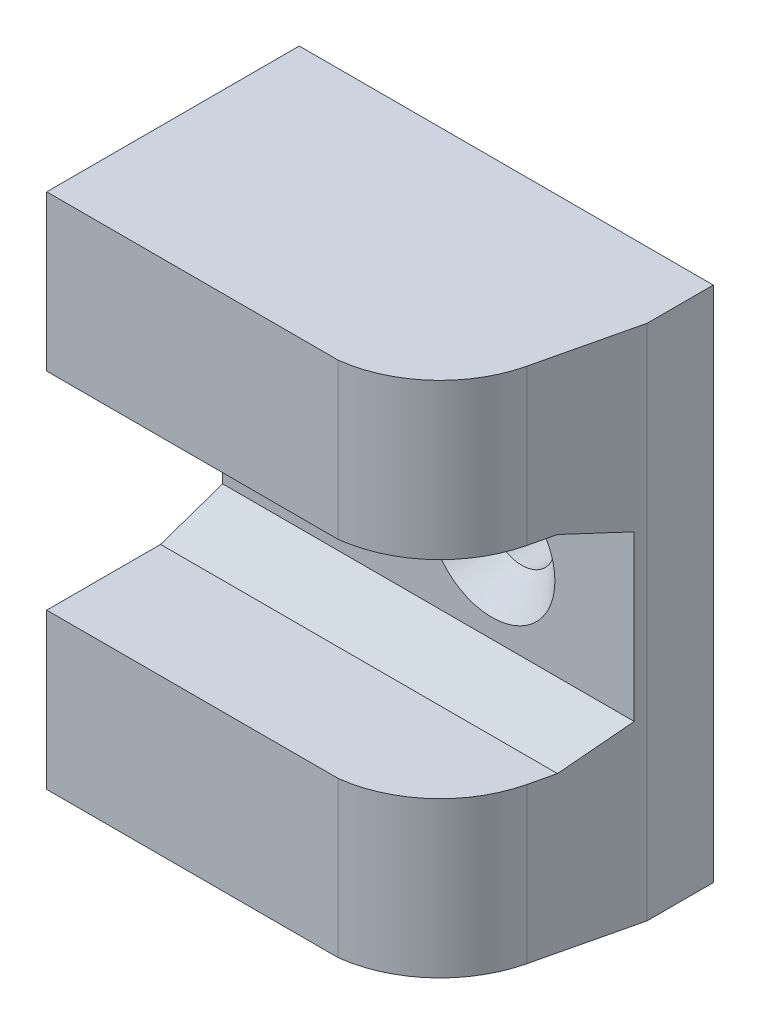
SolidWorks part; units mm, degrees
ref_plane "前视基准面" through (0, 0, 0) normal (0, 0, 1) x (1, 0, 0)
ref_plane "上视基准面" through (0, 0, 0) normal (0, 1, 0) x (1, 0, 0)
ref_plane "右视基准面" through (0, 0, 0) normal (1, 0, 0) x (0, 0, -1)
sketch "草图1" plane through (0, 0, 0) normal (0, 0, 1) x (1, 0, 0)
  line L0 (127, 105) -> (127, -105) construction
  line L1 (127, 80) -> (107, 80)
  line L2 (127, 80) -> (127, 105)
  line L4 (107, 80) -> (107, 105)
  line L5 (72, 105) -> (127, 105) construction
  line L6 (127, 105) -> (107, 105)
  dimension "D1" = 20
  dimension "D2" = 25
extrude "凸台-拉伸1" add sketch "草图1" along normal blind 12.2
sketch "草图2" plane through (0, 105, 0) normal (0, 1, 0) x (1, 0, 0)
  line L0 (127, -12.2) -> (127, 0) construction
  line L6 (125.8906, -7.896) -> (127, -3.196)
  line L8 (127, -3.196) -> (127, -12.2)
  line L10 (127, -12.2) -> (121.083, -12.2)
  line L11 (127, -12.2) -> (107, -12.2) construction
  arc A1 (121.083, -12.2) -> (125.8906, -7.896) centre (120.4, -6.6) ccw
  dimension "D1" = 5.917
  dimension "D2" = 5.6
  dimension "D3" = 6.6
  dimension "D4" = 4.7
extrude "切除-拉伸1" cut sketch "草图2" against normal blind 26.5
sketch "草图3" plane through (0, 0, 12.2) normal (0, 0, 1) x (1, 0, 0)
  line L0 (107, 92.5) -> (127, 92.5) construction
  line L1 (107, 105) -> (107, 80) construction
  line L4 (107, 97.5) -> (127, 97.5)
  line L5 (107, 97.5) -> (107, 87.5)
  line L6 (107, 87.5) -> (127, 87.5)
  line L7 (127, 97.5) -> (127, 87.5)
  line L8 (107, 97.5) -> (127, 87.5) construction
  line L9 (107, 87.5) -> (127, 97.5) construction
  point P6 (117, 92.5)
  dimension "D1" = 10
  dimension "D2" = 20
extrude "切除-拉伸2" cut sketch "草图3" against normal blind 8.5
sketch "草图4" plane through (0, 0, 3.7) normal (0, 0, 1) x (1, 0, 0)
  line L0 (107, 92.5) -> (126.881, 92.5) construction
  line L1 (107, 97.5) -> (107, 87.5) construction
  line L2 (126.881, 87.5) -> (126.881, 97.5) construction
  circle A0 centre (112, 92.5) radius 1.5
  circle A2 centre (120, 92.5) radius 1.5
  dimension "D1" = 3
  dimension "D2" = 8
  dimension "D3" = 5
hole_wizard "打孔尺寸(%根据)内六角花形半沉头螺钉的类型1" positions "草图7" profile "草图8" countersink size "M6" standard "GB" end condition through all
sketch "草图7" plane through (0, 0, 3.7) normal (0, 0, 1) x (1, 0, 0)
  point P0 (112, 92.5)
  point P3 (120, 92.5)
sketch "草图8" plane through (112, 92.5, 3.7) normal (1, 0, 0) x (0, -1, 0)
  line L0 (0, 0) -> (0, 3.7)
  line L1 (0, 3.7) -> (1.6, 3.7)
  line L2 (1.6, 3.7) -> (1.6, 1.45)
  line L3 (1.6, 1.45) -> (3.05, 0)
  line L5 (3.05, 0) -> (0, 0)
  line L6 (-1.6, 1.45) -> (-3.05, 0) construction
  line L11 (0, -6.35) -> (0, 107.95) construction
  dimension "通孔孔直径" = 3.2
  dimension "通孔孔深度" = 3.7
  dimension "近端锥形沉头孔直径" = 6.1
  dimension "近端锥形沉头孔角度" = 90
chamfer "倒角1" distance 3 angle 19 2 edges at (116.9405, 97.5, 3.7) (116.9405, 87.5, 3.7)
move or copy body "实体-移动/复制1" [suppressed] bodies to move or copy 109
